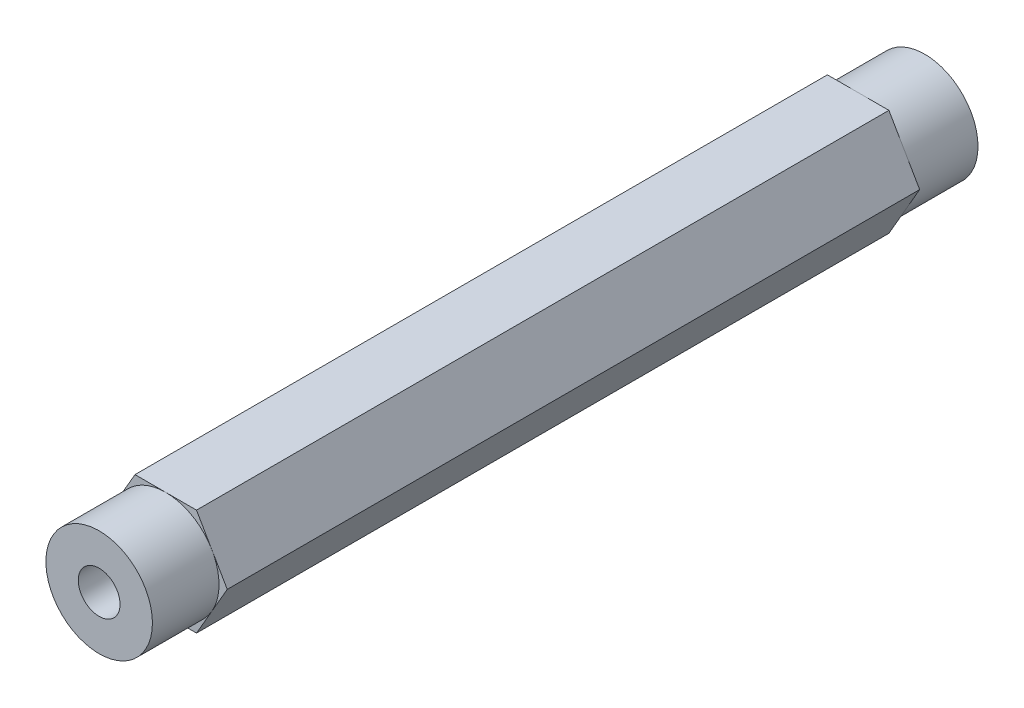
SolidWorks part; units mm, degrees
ref_plane "Front Plane" through (0, 0, 0) normal (0, 0, 1) x (1, 0, 0)
ref_plane "Top Plane" through (0, 0, 0) normal (0, 1, 0) x (1, 0, 0)
ref_plane "Right Plane" through (0, 0, 0) normal (1, 0, 0) x (0, 0, -1)
sketch "Sketch1" plane through (0, 0, 0) normal (0, 0, 1) x (1, 0, 0)
  line L1 (3.6662, 6.35) -> (-3.6662, 6.35)
  line L2 (-3.6662, 6.35) -> (-7.3323, 0)
  line L3 (-7.3323, 0) -> (-3.6662, -6.35)
  line L4 (-3.6662, -6.35) -> (3.6662, -6.35)
  line L5 (3.6662, -6.35) -> (7.3323, 0)
  line L6 (7.3323, 0) -> (3.6662, 6.35)
  circle A0 centre (0, 0) radius 6.35 construction
  circle A1 centre (0, 0) radius 2.4892
  point P1 (0, 6.35)
  dimension "D1" = 12.7
  dimension "D2" = 4.9784
extrude "Boss-Extrude1" add sketch "Sketch1" along normal mid plane 98.425
sketch "Sketch2" plane through (0, 0, 49.2125) normal (0, 0, 1) x (1, 0, 0)
  circle A0 centre (0, 0) radius 6.35
  dimension "D1" = 12.7
extrude "Cut-Extrude1" cut sketch "Sketch2" against normal blind 7.9375 flip side to cut
mirror "Mirror1" about plane through (0, 0, 0) normal (0, 0, 1) of "Cut-Extrude1"
